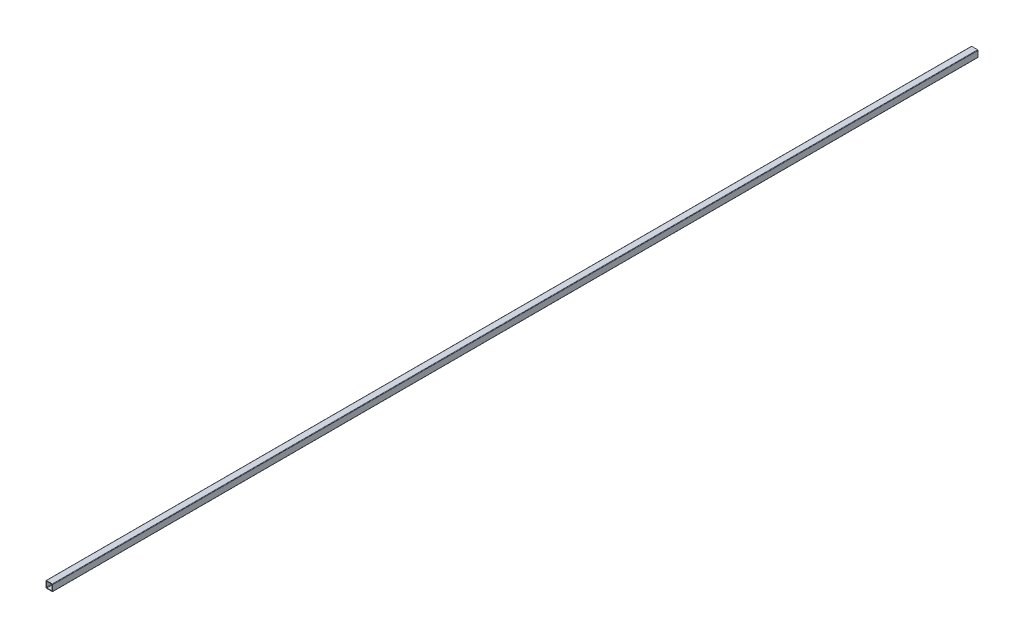
SolidWorks part; units mm, degrees
material "ASTM A500 Grade B Steel"
ref_plane "Front Plane" through (0, 0, 0) normal (0, 0, 1) x (1, 0, 0)
ref_plane "Top Plane" through (0, 0, 0) normal (0, 1, 0) x (1, 0, 0)
ref_plane "Right Plane" through (0, 0, 0) normal (1, 0, 0) x (0, 0, -1)
sketch "Sketch1" plane through (0, 0, 0) normal (0, 0, 1) x (1, 0, 0)
  line L0 (5.3086, -2.7686) -> (32.7914, -2.7686)
  line L1 (2.54, 0) -> (35.56, 0)
  line L2 (0, -2.54) -> (0, -35.56)
  line L3 (2.54, -38.1) -> (35.56, -38.1)
  line L4 (38.1, -2.54) -> (38.1, -35.56)
  line L5 (35.3314, -5.3086) -> (35.3314, -32.7914)
  line L6 (5.3086, -35.3314) -> (32.7914, -35.3314)
  line L7 (2.7686, -5.3086) -> (2.7686, -32.7914)
  line L8 (0, 0) -> (0, -38.1) construction
  line L9 (0, -38.1) -> (38.1, -38.1) construction
  line L10 (38.1, 0) -> (38.1, -38.1) construction
  line L11 (2.7686, -2.7686) -> (2.7686, -35.3314) construction
  line L12 (2.7686, -35.3314) -> (35.3314, -35.3314) construction
  line L13 (35.3314, -2.7686) -> (35.3314, -35.3314) construction
  line L14 (2.7686, -2.7686) -> (35.3314, -2.7686) construction
  line L15 (0, 0) -> (38.1, 0) construction
  arc A0 (0, -35.56) -> (2.54, -38.1) centre (2.54, -35.56) ccw
  arc A1 (38.1, -35.56) -> (35.56, -38.1) centre (35.56, -35.56) cw
  arc A2 (2.7686, -32.7914) -> (5.3086, -35.3314) centre (5.3086, -32.7914) ccw
  arc A3 (32.7914, -35.3314) -> (35.3314, -32.7914) centre (32.7914, -32.7914) ccw
  arc A4 (35.3314, -5.3086) -> (32.7914, -2.7686) centre (32.7914, -5.3086) ccw
  arc A5 (38.1, -2.54) -> (35.56, 0) centre (35.56, -2.54) ccw
  arc A6 (0, -2.54) -> (2.54, 0) centre (2.54, -2.54) cw
  arc A7 (5.3086, -2.7686) -> (2.7686, -5.3086) centre (5.3086, -5.3086) ccw
  point P12 (0, -38.1)
  dimension "D4" = 2.54
  dimension "D3" = 2.7686
extrude "Boss-Extrude1" add sketch "Sketch1" along normal blind 5243.8
sketch "Sketch2" plane through (0, -38.1, 0) normal (0, -1, 0) x (-1, 0, 0)
  line L0 (-19.05, 0) -> (-19.05, -5243.8) construction
  line L1 (-2.54, 0) -> (-35.56, 0) construction
  line L2 (-2.54, -5243.8) -> (-35.56, -5243.8) construction
